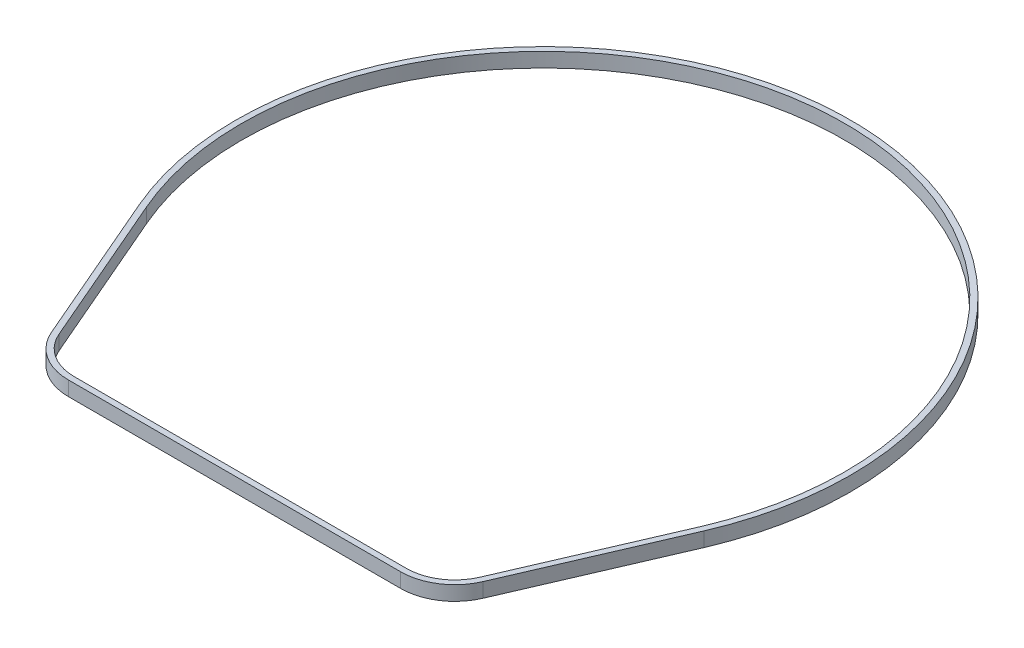
SolidWorks part; units mm, degrees
ref_plane "Front Plane" through (0, 0, 0) normal (0, 0, 1) x (1, 0, 0)
ref_plane "Top Plane" through (0, 0, 0) normal (0, 1, 0) x (1, 0, 0)
ref_plane "Right Plane" through (0, 0, 0) normal (1, 0, 0) x (0, 0, -1)
sketch "Sketch1" plane through (0, 0, 0) normal (0, 1, 0) x (1, 0, 0)
  line L0 (-34.4227, -62.75) -> (34.4227, -62.75)
  line L1 (43.605, -56.7106) -> (57.389, -24.7538)
  line L2 (0, 0) -> (0, -62.75) construction
  line L3 (0, 0) -> (57.389, -24.7538) construction
  line L4 (-43.605, -56.7106) -> (-57.389, -24.7538)
  line L5 (44.7069, -57.1859) -> (58.4909, -25.2291)
  line L6 (-34.4227, -63.95) -> (34.4227, -63.95)
  line L7 (-44.7069, -57.1859) -> (-58.4909, -25.2291)
  circle A0 centre (0, 0) radius 62.5
  arc A1 (34.4227, -62.75) -> (43.605, -56.7106) centre (34.4227, -52.75) ccw
  arc A2 (-43.605, -56.7106) -> (-34.4227, -62.75) centre (-34.4227, -52.75) ccw
  arc A3 (34.4227, -63.95) -> (44.7069, -57.1859) centre (34.4227, -52.75) ccw
  arc A4 (-44.7069, -57.1859) -> (-34.4227, -63.95) centre (-34.4227, -52.75) ccw
  arc A6 (58.4909, -25.2291) -> (-58.4909, -25.2291) centre (0, 0) ccw
  point P10 (41, -62.75)
  point P13 (-41, -62.75)
  dimension "D1" = 125
  dimension "D4" = 10
  dimension "D2" = 41
  dimension "D3" = 90
  dimension "D6" = 62.75
  dimension "D5" = 1.2
extrude "Boss-Extrude1" add sketch "Sketch1" along normal blind 3 contours L5 A6 L7 A4 L6 A3 A2 L4 A0 L1 A1 L0
